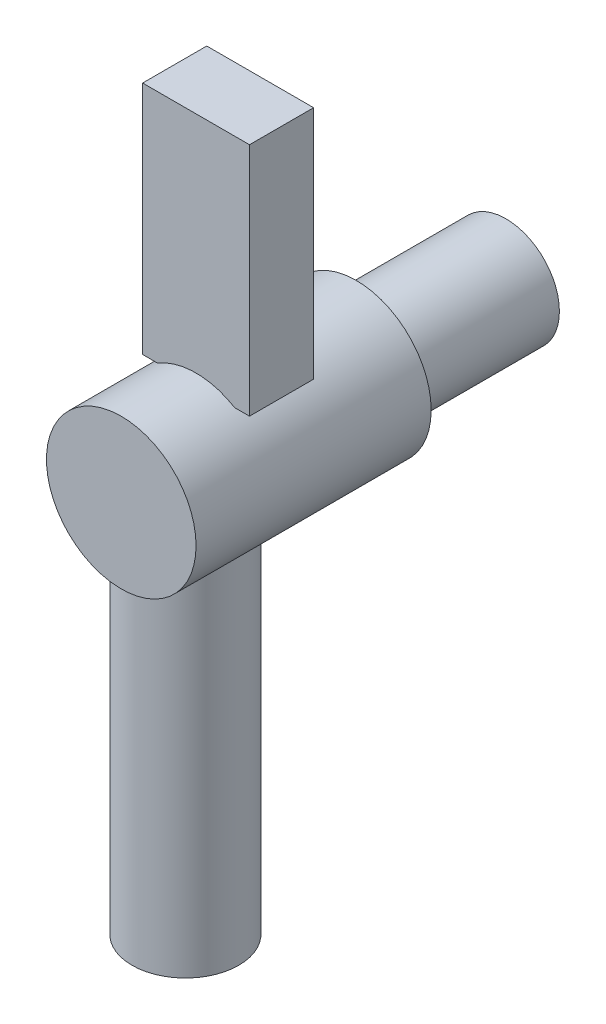
SolidWorks part; units mm, degrees
ref_plane "Front Plane" through (0, 0, 0) normal (0, 0, 1) x (1, 0, 0)
ref_plane "Top Plane" through (0, 0, 0) normal (0, 1, 0) x (1, 0, 0)
ref_plane "Right Plane" through (0, 0, 0) normal (1, 0, 0) x (0, 0, -1)
other "Configuration Table"
sketch "Sketch1" plane through (0, 0, 0) normal (0, 0, 1) x (1, 0, 0)
  circle A0 centre (0, 0) radius 5
  dimension "D1" = 10
extrude "Spigot" add sketch "Sketch1" along normal blind 14
sketch "Sketch2" plane through (0, 0, 0) normal (0, 0, 1) x (1, 0, 0)
  circle A0 centre (0, 0) radius 7
  dimension "D1" = 14
extrude "Body" add sketch "Sketch2" along normal blind 22 from offset 14
sketch "Sketch3" plane through (0, 0, 0) normal (0, 1, 0) x (1, 0, 0)
  circle A0 centre (0, -30) radius 5
  dimension "D1" = 10
extrude "Spout" add sketch "Sketch3" along normal blind 38 from offset 38
sketch "Sketch4" plane through (0, 0, 0) normal (0, 1, 0) x (1, 0, 0)
  line L0 (-5, -29) -> (5, -29)
  line L1 (5, -29) -> (5, -23)
  line L2 (5, -23) -> (-5, -23)
  line L3 (-5, -23) -> (-5, -29)
extrude "Lever" add sketch "Sketch4" along normal blind 22 from offset 6
equation "\"Jar_OD\"= 90  'ASSUMED - Part G fallback - jar outer diameter"
equation "\"Jar_H\"= 120  'ASSUMED - Part G fallback - jar height"
equation "\"Pump_L\"= 45  'ASSUMED - Part G fallback"
equation "\"Pump_W\"= 24  'ASSUMED - Part G fallback"
equation "\"Pump_H\"= 33  'ASSUMED - Part G fallback"
equation "\"Pump_Outlet_OD\"= 7.5  'ASSUMED - Part G fallback"
equation "\"Tube_OD\"= 8  'ASSUMED - Part G fallback"
equation "\"Tube_ID\"= 6  'ASSUMED - Part G fallback"
equation "\"TDS_Body_Dia\"= 12  'ASSUMED - Part G fallback"
equation "\"TDS_Wet_Len\"= 45  'ASSUMED - Part G fallback - length in water"
equation "\"DS_Tube_Dia\"= 6  'ASSUMED - Part G fallback"
equation "\"DS_Tube_Len\"= 50  'ASSUMED - Part G fallback"
equation "\"ORP_Body_Dia\"= 12  'ASSUMED - Part G fallback"
equation "\"ORP_Body_Len\"= 150  'ASSUMED - Part G fallback"
equation "\"ORP_Cap_Dia\"= 16  'ASSUMED - Part G fallback"
equation "\"Turb_W\"= 33  'ASSUMED - Part G fallback - head width"
equation "\"Turb_D\"= 28  'ASSUMED - Part G fallback - head depth"
equation "\"Turb_H\"= 30  'ASSUMED - Part G fallback - head height"
equation "\"Turb_Slot_W\"= 10  'ASSUMED - Part G fallback - slot width"
equation "\"Flow_L\"= 62  'ASSUMED - Part G fallback YF-S201"
equation "\"Flow_W\"= 36  'ASSUMED - Part G fallback"
equation "\"Flow_H\"= 35  'ASSUMED - Part G fallback"
equation "\"Thread_G12_OD\"= 20.955  'ASSUMED - Part G fallback thread G1/2 (major diameter)"
equation "\"Valve_L\"= 75  'ASSUMED - Part G fallback"
equation "\"Valve_W\"= 45  'ASSUMED - Part G fallback"
equation "\"Valve_H\"= 60  'ASSUMED - Part G fallback"
equation "\"Tee_L\"= 40  'ASSUMED - Part G fallback - overall length"
equation "\"Tee_Branch_L\"= 25  'ASSUMED - Part G fallback"
equation "\"Tee_OD\"= 12  'ASSUMED - Part G fallback"
equation "\"LED_Board_L\"= 20  'ASSUMED - Part G fallback"
equation "\"LED_Board_W\"= 20  'ASSUMED - Part G fallback - LED at centre"
equation "\"GUVA_L\"= 20  'ASSUMED - Part G fallback"
equation "\"GUVA_W\"= 12  'ASSUMED - Part G fallback - sensor at centre"
equation "\"Reed_L\"= 27  'ASSUMED - Part G fallback MC-38 half"
equation "\"Reed_W\"= 14  'ASSUMED - Part G fallback"
equation "\"Reed_H\"= 8  'ASSUMED - Part G fallback"
equation "\"ESP_L\"= 51  'ASSUMED - Part G fallback"
equation "\"ESP_W\"= 28  'ASSUMED - Part G fallback"
equation "\"TFT_L\"= 58  'ASSUMED - Part G fallback - board"
equation "\"TFT_W\"= 35  'ASSUMED - Part G fallback - board"
equation "\"TFT_Win_L\"= 35  'ASSUMED - Part G fallback - visible window"
equation "\"TFT_Win_W\"= 28  'ASSUMED - Part G fallback - visible window"
equation "\"Relay_L\"= 50  'ASSUMED - Part G fallback"
equation "\"Relay_W\"= 26  'ASSUMED - Part G fallback"
equation "\"Relay_H\"= 19  'ASSUMED - Part G fallback"
equation "\"Mosfet_L\"= 34  'ASSUMED - Part G fallback"
equation "\"Mosfet_W\"= 17  'ASSUMED - Part G fallback"
equation "\"Mosfet_H\"= 12  'ASSUMED - Part G fallback"
equation "\"TDS_Board_L\"= 42  'ASSUMED - Part G fallback"
equation "\"TDS_Board_W\"= 32  'ASSUMED - Part G fallback"
equation "\"Turb_Board_L\"= 38  'ASSUMED - Part G fallback"
equation "\"Turb_Board_W\"= 28  'ASSUMED - Part G fallback"
equation "\"BNC_Thread_Dia\"= 9.5  'ASSUMED - Part G fallback"
equation "\"Plate_L\"= 420  'ASSUMED - Part G fallback"
equation "\"Plate_W\"= 297  'ASSUMED - Part G fallback"
equation "\"Plate_T\"= 6  'ASSUMED - Part G fallback"
equation "\"Booster_L\"= 150  'ASSUMED - Part G fallback - booster pump"
equation "\"Booster_W\"= 95  'ASSUMED - Part G fallback"
equation "\"Booster_H\"= 100  'ASSUMED - Part G fallback"
equation "\"PTube_OD\"= 6.35  'ASSUMED - Part G fallback - product tube 1/4 inch"
equation "\"Qz_Out\"= 12  'ASSUMED - Part G fallback - quartz channel outside square"
equation "\"Qz_Path\"= 10  'ASSUMED - Part G fallback - quartz channel inside light path"
equation "\"Qz_L\"= 40  'ASSUMED - Part G fallback - quartz channel length"
equation "\"LED860_Dia\"= 5  'ASSUMED - Part G fallback - 860 nm LED"
equation "\"BPW_L\"= 5.4  'ASSUMED - Part G fallback - BPW34"
equation "\"BPW_W\"= 4.3  'ASSUMED - Part G fallback - BPW34"
equation "\"Cart_Dia\"= 50  'ASSUMED - Part G fallback - sediment and pre-carbon cartridges"
equation "\"Cart_L\"= 255  'ASSUMED - Part G fallback"
equation "\"UF_Dia\"= 50  'ASSUMED - Part G fallback - UF cartridge"
equation "\"UF_L\"= 260  'ASSUMED - Part G fallback"
equation "\"RO_Dia\"= 62  'ASSUMED - Part G fallback - RO membrane housing"
equation "\"RO_L\"= 300  'ASSUMED - Part G fallback"
equation "\"UVC_Dia\"= 40  'ASSUMED - Part G fallback - UV-C chamber"
equation "\"UVC_L\"= 300  'ASSUMED - Part G fallback"
equation "\"Tank_W\"= 260  'ASSUMED - Part G fallback - storage tank"
equation "\"Tank_D\"= 160  'ASSUMED - Part G fallback"
equation "\"Tank_H\"= 300  'ASSUMED - Part G fallback"
equation "\"Cab_W\"= 400  'ASSUMED - Part G fallback - purifier cabinet"
equation "\"Cab_D\"= 270  'ASSUMED - Part G fallback"
equation "\"Cab_H\"= 560  'ASSUMED - Part G fallback"
equation "\"ORP_Board_L\"= 40  'ASSUMED - Part G fallback - ORP buffer board"
equation "\"ORP_Board_W\"= 30  'ASSUMED - Part G fallback"
equation "\"Opt_Board_L\"= 50  'ASSUMED - Part G fallback - optical front-end board"
equation "\"Opt_Board_W\"= 40  'ASSUMED - Part G fallback"
equation "\"Buck_L\"= 43  'ASSUMED - Part G fallback - 12 V to 5 V buck module"
equation "\"Buck_W\"= 21  'ASSUMED - Part G fallback"
equation "\"Buck_H\"= 14  'ASSUMED - Part G fallback"
equation "\"BB_L\"= 165  'ASSUMED - Part G fallback - breadboard (As_Built_R3 only)"
equation "\"BB_W\"= 55  'ASSUMED - Part G fallback"
equation "\"BB_H\"= 10  'ASSUMED - Part G fallback"
equation "\"Cuv_W\"= 12.5  'ASSUMED - old R3 cuvette (station suppressed in SS4)"
equation "\"Cuv_D\"= 12.5  'ASSUMED - old R3 cuvette (station suppressed in SS4)"
equation "\"Cuv_H\"= 45  'ASSUMED - old R3 cuvette (station suppressed in SS4)"
equation "\"Probe_Clr\"= 0.3  'DESIGN VALUE - Part C rule 3 - printed probe hole = diameter + 0.3"
equation "\"Label_H\"= 0.6  'DESIGN VALUE - Part D - raised label height"
